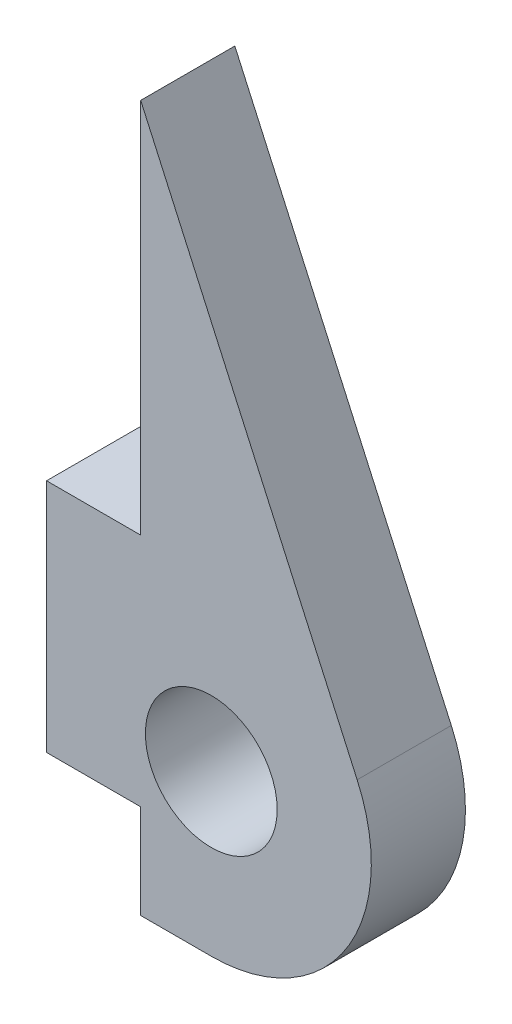
SolidWorks part; units mm, degrees
ref_plane "Front Plane" through (0, 0, 0) normal (0, 0, 1) x (1, 0, 0)
ref_plane "Top Plane" through (0, 0, 0) normal (0, 1, 0) x (1, 0, 0)
ref_plane "Right Plane" through (0, 0, 0) normal (1, 0, 0) x (0, 0, -1)
sketch "Sketch1" plane through (0, 0, 0) normal (0, 0, 1) x (1, 0, 0)
  line L0 (-1.5, 16.1222) -> (-1.5, -6.5252) construction
  line L1 (0, 0) -> (-1.5, 0) construction
  line L2 (0, 0) -> (1.4, 0) construction
  line L3 (1.4, 0) -> (3.4, 0) construction
  line L4 (-1.5, -3.4) -> (-1.5, -1.4)
  line L5 (-1.5, 11.6) -> (3.0996, 1.3974)
  line L6 (0, -3.4) -> (-1.5, -3.4)
  line L7 (-1.5, 3.6) -> (-3.5, 3.6)
  line L8 (-3.5, 3.6) -> (-3.5, -1.4)
  line L9 (-3.5, -1.4) -> (-1.5, -1.4)
  line L10 (-1.5, 3.6) -> (-1.5, 11.6)
  circle A0 centre (0, 0) radius 1.4
  arc A1 (0, -3.4) -> (3.0996, 1.3974) centre (0, 0) ccw
  dimension "D1" = 2.8
  dimension "D2" = 1.5
  dimension "D3" = 2
  dimension "D4" = 15
  dimension "D5" = 2
  dimension "D6" = 2
  dimension "D7" = 5
extrude "Boss-Extrude1" add sketch "Sketch1" along normal blind 2
